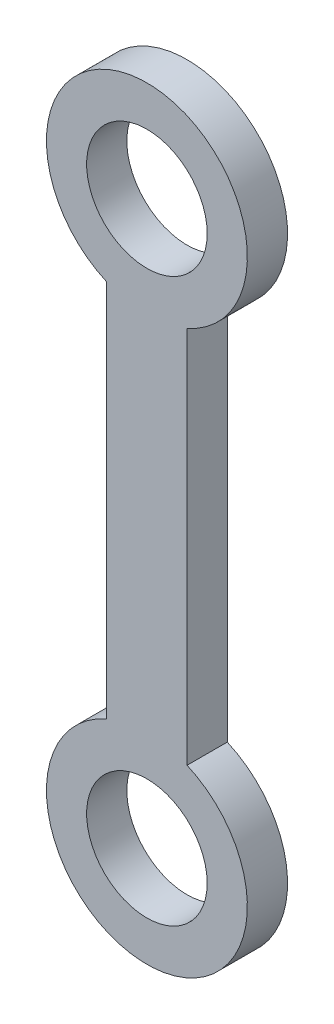
SolidWorks part; units mm, degrees
ref_plane "Plan de face" through (0, 0, 0) normal (0, 0, 1) x (1, 0, 0)
ref_plane "Plan de dessus" through (0, 0, 0) normal (0, 1, 0) x (1, 0, 0)
ref_plane "Plan de droite" through (0, 0, 0) normal (1, 0, 0) x (0, 0, -1)
sketch "Esquisse1" plane through (0, 0, 0) normal (0, 0, 1) x (1, 0, 0)
  line L0 (0, 140) -> (0, 0) construction
  line L1 (-10, 117.0871) -> (-10, 22.9129)
  line L2 (0, 140) -> (0, 165) construction
  line L3 (0, 0) -> (0, -25) construction
  line L4 (10, 117.0871) -> (10, 22.9129)
  circle A0 centre (0, 0) radius 15
  circle A1 centre (0, 140) radius 15
  arc A2 (-10, 117.0871) -> (10, 117.0871) centre (0, 140) cw
  arc A3 (-10, 22.9129) -> (10, 22.9129) centre (0, 0) ccw
  dimension "D2" = 30
  dimension "D3" = 30
  dimension "D4" = 10
  dimension "D5" = 10
  dimension "D1" = 140
  dimension "D6" = 10
extrude "Boss.-Extru.1" add sketch "Esquisse1" along normal blind 10
